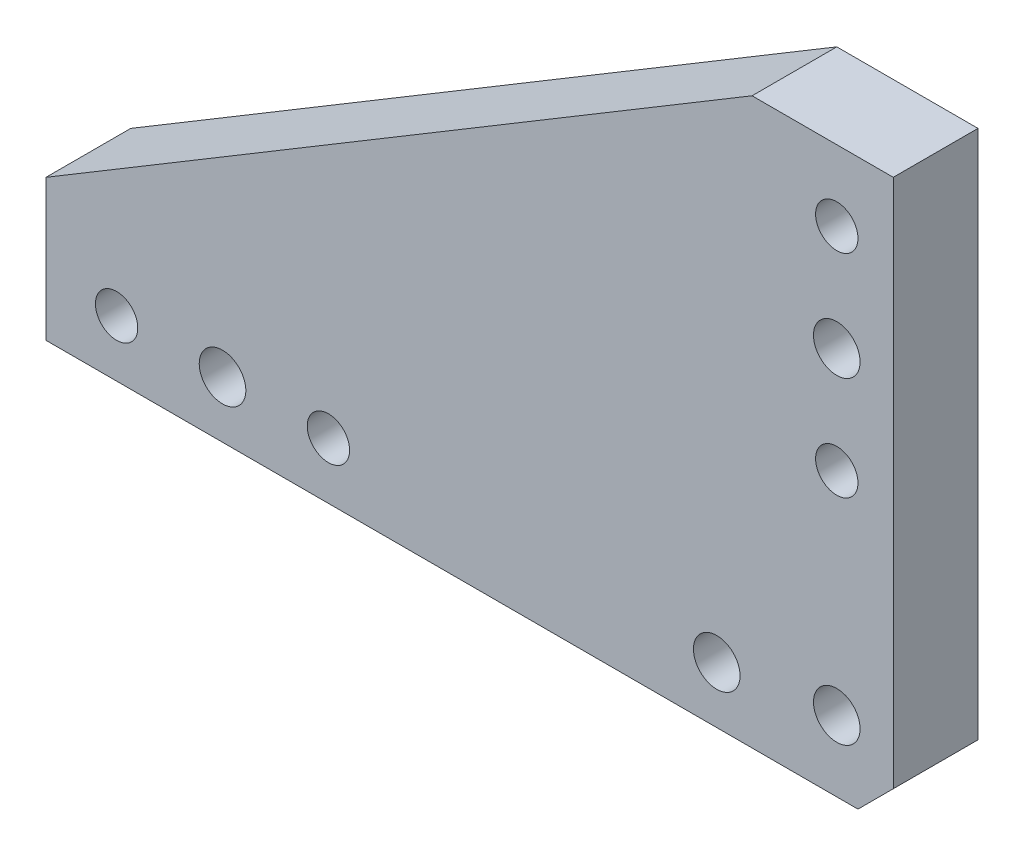
SolidWorks part; units mm, degrees
material "Q235A"
ref_plane "前视" through (0, 0, 0) normal (0, 0, 1) x (1, 0, 0)
ref_plane "上视" through (0, 0, 0) normal (0, 1, 0) x (1, 0, 0)
ref_plane "右视" through (0, 0, 0) normal (1, 0, 0) x (0, 0, -1)
sketch "草图1" plane through (0, 0, 0) normal (0, 0, 1) x (1, 0, 0)
  line L1 (60, -40) -> (-60, -40)
  line L2 (60, -40) -> (60, 40)
  line L3 (60, 40) -> (-60, 40)
  line L4 (-60, -40) -> (-60, 40)
  line L5 (60, -40) -> (-60, 40) construction
  line L6 (60, 40) -> (-60, -40) construction
  point P0 (0, 0)
  dimension "D1" = 80
  dimension "D2" = 120
extrude "凸台-拉伸1" add sketch "草图1" along normal blind 12
chamfer "倒角1" distance 100 distance2 60 1 edges at (-60, 40, 6)
chamfer "倒角2" distance 5 angle 45 1 edges at (60, -40, 6)
hole_wizard "大小mm 暗销孔1" positions "草图3" profile "草图2" hole size "Ø6.0" standard "GB" end condition through all
sketch "草图3" plane through (0, 0, 0) normal (0, 0, -1) x (-1, 0, 0)
  line L0 (-60, -35) -> (-60, 40) construction
  line L1 (-60, 40) -> (-40, 40) construction
  line L2 (60, -20) -> (60, -40) construction
  line L3 (60, -40) -> (-55, -40) construction
  point P0 (50, -32)
  point P2 (20, -32)
  point P4 (-52, 30)
  point P6 (-52, 0)
  dimension "D1" = 8
  dimension "D2" = 10
  dimension "D3" = 30
  dimension "D4" = 30
  dimension "D5" = 10
  dimension "D6" = 8
sketch "草图2" plane through (-50, -32, 0) normal (1, 0, 0) x (0, 1, 0)
  line L0 (0, 0) -> (0, 12)
  line L1 (0, 12) -> (3, 12)
  line L2 (3, 12) -> (3, 0)
  line L5 (3, 0) -> (0, 0)
  line L11 (0, -6.35) -> (0, 107.95) construction
  dimension "通孔孔直径" = 6
  dimension "通孔孔深度" = 12
hole_wizard "M6 间隙孔1" positions "草图5" profile "草图4" hole size "M6" standard "GB" end condition through all
sketch "草图5" plane through (0, 0, 0) normal (0, 0, -1) x (-1, 0, 0)
  line L0 (-60, -35) -> (-60, 40) construction
  line L1 (60, -40) -> (-55, -40) construction
  circle A0 centre (-52, 0) radius 3 construction
  circle A1 centre (50, -32) radius 3 construction
  point P0 (-52, 15)
  point P2 (-52, -30)
  point P4 (-35, -32)
  point P6 (35, -32)
  dimension "D1" = 15
  dimension "D2" = 8
  dimension "D3" = 45
  dimension "D4" = 70
  dimension "D5" = 15
  dimension "D6" = 8
sketch "草图4" plane through (52, 15, 0) normal (1, 0, 0) x (0, 1, 0)
  line L0 (0, 0) -> (0, 12)
  line L1 (0, 12) -> (3.3, 12)
  line L2 (3.3, 12) -> (3.3, 0)
  line L5 (3.3, 0) -> (0, 0)
  line L11 (0, -6.35) -> (0, 107.95) construction
  dimension "通孔孔直径" = 6.6
  dimension "通孔孔深度" = 12
